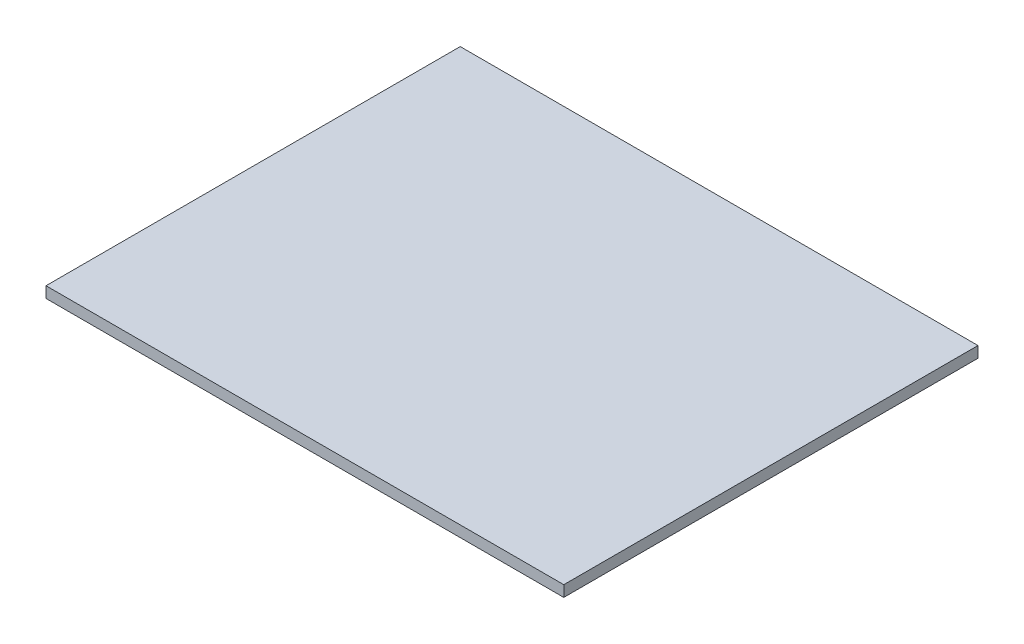
SolidWorks part; units mm, degrees
ref_plane "Front Plane" through (0, 0, 0) normal (0, 0, 1) x (1, 0, 0)
ref_plane "Top Plane" through (0, 0, 0) normal (0, 1, 0) x (1, 0, 0)
ref_plane "Right Plane" through (0, 0, 0) normal (1, 0, 0) x (0, 0, -1)
sketch "Sketch1" plane through (0, 0, 0) normal (0, 1, 0) x (1, 0, 0)
  line L1 (-37.5, -30) -> (37.5, -30)
  line L2 (-37.5, -30) -> (-37.5, 30)
  line L3 (-37.5, 30) -> (37.5, 30)
  line L4 (37.5, -30) -> (37.5, 30)
  line L5 (-37.5, -30) -> (37.5, 30) construction
  line L6 (-37.5, 30) -> (37.5, -30) construction
  point P0 (0, 0)
  dimension "D1" = 60
  dimension "D2" = 75
extrude "Boss-Extrude1" add sketch "Sketch1" along normal blind 1.6
